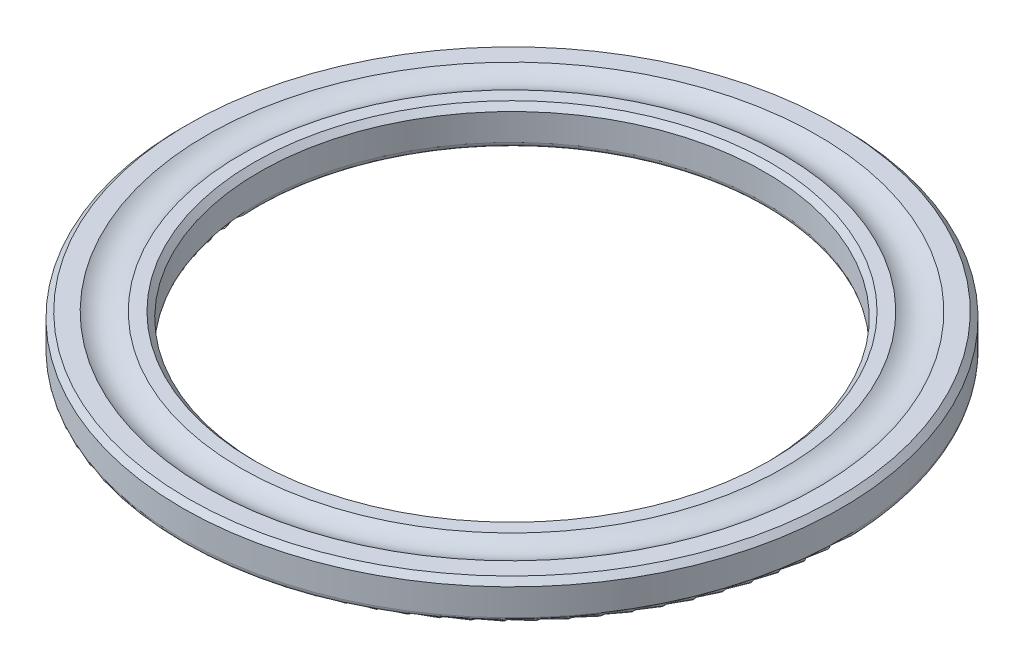
SolidWorks part; units mm, degrees
ref_plane "Front Plane" through (0, 0, 0) normal (0, 0, 1) x (1, 0, 0)
ref_plane "Top Plane" through (0, 0, 0) normal (0, 1, 0) x (1, 0, 0)
ref_plane "Right Plane" through (0, 0, 0) normal (1, 0, 0) x (0, 0, -1)
ref_plane "Plane1" through (0, 0, 0) normal (0, 0, -1) x (-1, 0, 0)
sketch "Sketch1" plane through (0, 0, 0) normal (0, 0, -1) x (-1, 0, 0)
  line L0 (-59, 0) -> (-47, 0)
  line L1 (-46, 1) -> (-46, 5.8724)
  line L2 (-46, 5.8724) -> (-47, 6.8724)
  line L3 (-47, 6.8724) -> (-49.4043, 6.8724)
  line L4 (-55.5957, 6.8724) -> (-59, 6.8724)
  line L5 (-59, 6.8724) -> (-60, 5.8724)
  line L6 (-60, 5.8724) -> (-60, 1)
  line L7 (0, 0) -> (0, 6.8724) construction
  arc A0 (-47, 0) -> (-46, 1) centre (-47, 1) ccw
  arc A1 (-49.4043, 6.8724) -> (-55.5957, 6.8724) centre (-52.5, 11) cw
  arc A2 (-60, 1) -> (-59, 0) centre (-59, 1) ccw
  dimension "D1" = 5.1595
  dimension "D2" = 14
  dimension "D3" = 6.1914
revolve "Revolve1" add sketch "Sketch1" angle 360 about L7
